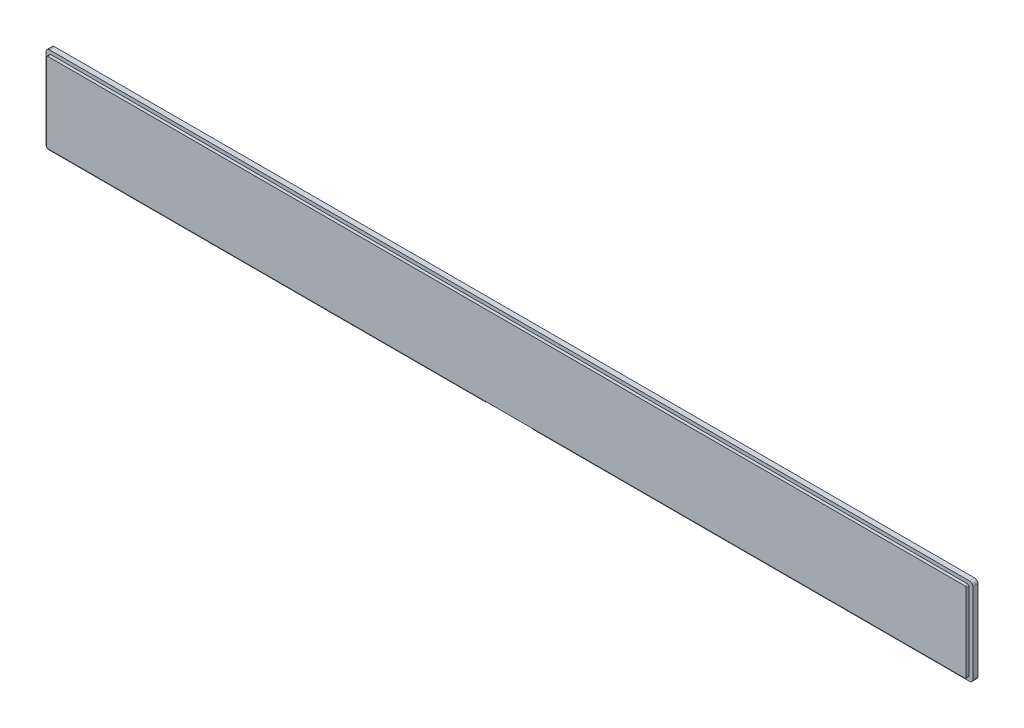
SolidWorks part; units mm, degrees
material "ABS_Black"
ref_plane "Přední rovina" through (0, 0, 0) normal (0, 0, 1) x (1, 0, 0)
ref_plane "Horní rovina" through (0, 0, 0) normal (0, 1, 0) x (1, 0, 0)
ref_plane "Pravá rovina" through (0, 0, 0) normal (1, 0, 0) x (0, 0, -1)
sketch "Skica1" plane through (0, 0, 0) normal (0, 0, 1) x (1, 0, 0)
  line L1 (213.25, -20) -> (-213.25, -20)
  line L2 (213.25, -20) -> (213.25, 20)
  line L3 (213.25, 20) -> (-213.25, 20)
  line L4 (-213.25, -20) -> (-213.25, 20)
  line L5 (213.25, -20) -> (-213.25, 20) construction
  line L6 (213.25, 20) -> (-213.25, -20) construction
  point P0 (0, 0)
  dimension "D1" = 426.5
  dimension "D2" = 40
extrude "Přidat vysunutím1" add sketch "Skica1" along normal blind 2.4
sketch "Skica2" plane through (0, 0, 2.4) normal (0, 0, 1) x (1, 0, 0)
  line L2 (-211.6, 18.4) -> (211.6, 18.4)
  line L3 (-211.6, 18.4) -> (-211.6, -18.4)
  line L4 (-211.6, -18.4) -> (211.6, -18.4)
  line L5 (211.6, 18.4) -> (211.6, -18.4)
  line L6 (-211.6, 18.4) -> (211.6, -18.4) construction
  line L7 (-211.6, -18.4) -> (211.6, 18.4) construction
  point P2 (0, 0)
  dimension "D1" = 36.8
  dimension "D2" = 423.2
extrude "Přidat vysunutím2" add sketch "Skica2" along normal blind 1.4
fillet "Zaoblit1" radius 1.5 4 edges at (-213.25, -20, 1.2) (-213.25, 20, 1.2) (213.25, -20, 1.2) (213.25, 20, 1.2)
fillet "Zaoblit2" radius 0.5 4 edges at (211.6, 18.4, 3.1) (211.6, -18.4, 3.1) (-211.6, -18.4, 3.1) (-211.6, 18.4, 3.1)
sketch "Skica3" plane through (0, 0, 2.4) normal (0, 0, 1) x (1, 0, 0)
  line L0 (0, 0) -> (0, -25.2092) construction
  line L1 (-11, -17.4751) -> (-11, -21.9838) construction
  line L2 (-12.2287, -19) -> (14.7393, -19) construction
  line L3 (-211.75, -20) -> (211.75, -20) construction
  line L4 (0, -19) -> (-10, -19)
  line L5 (0, -19) -> (10, -19)
  line L6 (11, -17.4751) -> (11, -21.9838) construction
  line L7 (11, -20) -> (11, -20.1169)
  line L8 (11, -20.1169) -> (-11, -20.1169)
  line L9 (-11, -20.1169) -> (-11, -20)
  arc A0 (-11, -20) -> (-10, -19) centre (-11, -19) ccw
  arc A1 (11, -20) -> (10, -19) centre (11, -19) cw
  dimension "D1" = 1
  dimension "D2" = 11
  dimension "D3" = 11
extrude "Odebrat vysunutím1" cut sketch "Skica3" against normal through all
